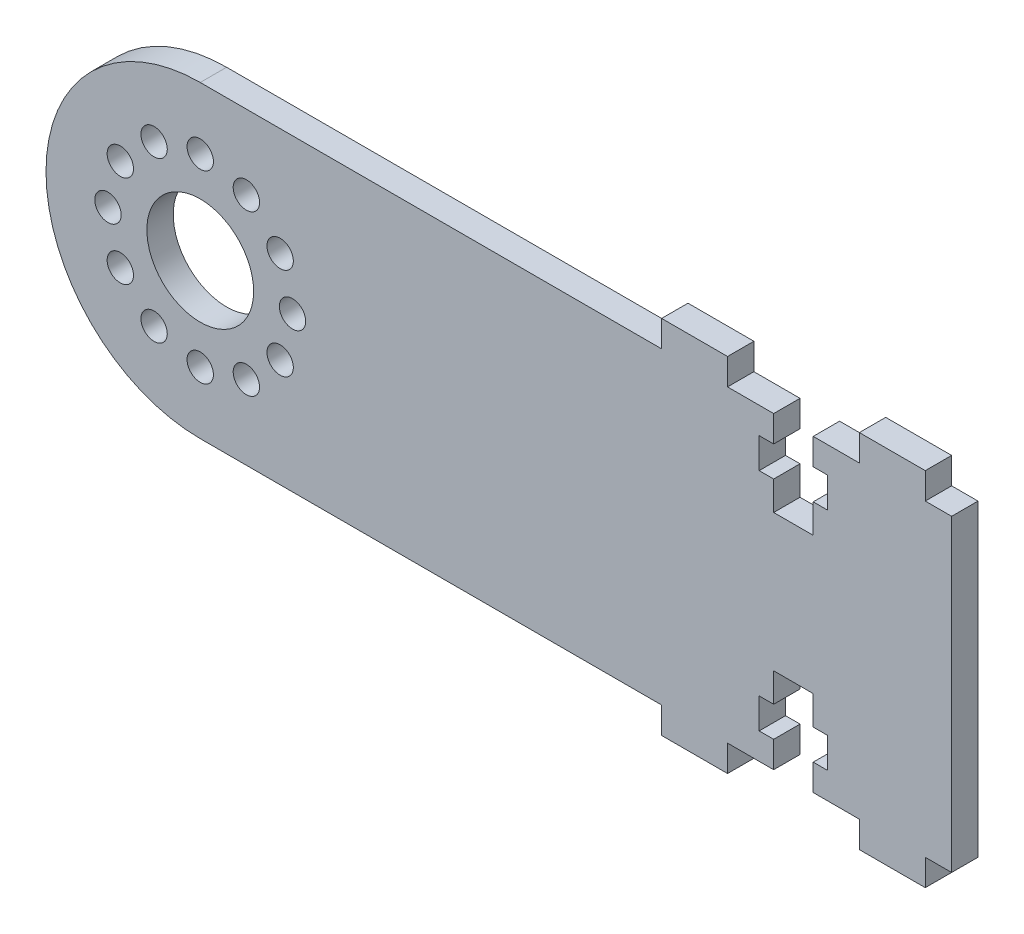
SolidWorks part; units mm, degrees
ref_plane "Front Plane" through (0, 0, 0) normal (0, 0, 1) x (1, 0, 0)
ref_plane "Top Plane" through (0, 0, 0) normal (0, 1, 0) x (1, 0, 0)
ref_plane "Right Plane" through (0, 0, 0) normal (1, 0, 0) x (0, 0, -1)
sketch "Sketch1" plane through (0, 0, 0) normal (0, 0, 1) x (1, 0, 0)
  line L0 (0, 11.7) -> (57, 11.7) construction
  line L1 (57, 11.7) -> (57, -11.7)
  line L2 (57, -11.7) -> (0, -11.7) construction
  line L3 (0, 0) -> (57, 0) construction
  line L4 (0, 11.7) -> (35, 11.7)
  line L5 (55, 11.7) -> (57, 11.7)
  line L6 (57, -11.7) -> (55, -11.7)
  line L7 (35, -11.7) -> (0, -11.7)
  arc A13 (0, 11.7) -> (0, -11.7) centre (0, 0) ccw
  point P2 (-45.8343, 7.2101)
  point P11 (-44.7074, 6.255)
  line B0 (0, 0) -> (7, 0) construction
  circle B1 centre (0, 0) radius 4.05
  circle B2 centre (7, 0) radius 1
  circle B3 centre (6.0622, -3.5) radius 1
  circle B4 centre (3.5, -6.0622) radius 1
  circle B5 centre (0, -7) radius 1
  circle B6 centre (-3.5, -6.0622) radius 1
  circle B7 centre (-6.0622, -3.5) radius 1
  circle B8 centre (-7, 0) radius 1
  circle B9 centre (-6.0622, 3.5) radius 1
  circle B10 centre (-3.5, 6.0622) radius 1
  circle B11 centre (0, 7) radius 1
  circle B12 centre (3.5, 6.0622) radius 1
  circle B13 centre (6.0622, 3.5) radius 1
  line B14 (45, -11.7) -> (45, -5.2) construction
  line B15 (43.5, -11.7) -> (40, -11.7)
  line B16 (40, -13.7) -> (35, -13.7)
  line B17 (35, -13.7) -> (35, -11.7)
  line B18 (40, -13.7) -> (40, -11.7)
  line B19 (46.5, -11.7) -> (50, -11.7)
  line B20 (50, -11.7) -> (50, -13.7)
  line B21 (50, -13.7) -> (55, -13.7)
  line B22 (55, -13.7) -> (55, -11.7)
  line B23 (43.5, -11.7) -> (46.5, -11.7) construction
  line B24 (46.5, -11.7) -> (46.5, -9.7)
  line B25 (46.5, -7.4) -> (47.6, -7.4)
  line B26 (42.4, -9.7) -> (42.4, -7.4)
  line B27 (47.6, -9.7) -> (46.5, -9.7)
  line B28 (46.5, -7.4) -> (46.5, -5.2)
  line B29 (46.5, -5.2) -> (43.5, -5.2)
  line B30 (43.5, -5.2) -> (43.5, -7.4)
  line B31 (43.5, -9.7) -> (42.4, -9.7)
  line B32 (47.6, -7.4) -> (47.6, -9.7)
  line B33 (42.4, -7.4) -> (43.5, -7.4)
  line B34 (43.5, -9.7) -> (43.5, -11.7)
  line B35 (45, -5.2) -> (45, -11.7) construction
  line B36 (45, 11.7) -> (45, 5.2) construction
  line B37 (43.5, 11.7) -> (40, 11.7)
  line B38 (40, 13.7) -> (35, 13.7)
  line B39 (35, 13.7) -> (35, 11.7)
  line B40 (40, 13.7) -> (40, 11.7)
  line B41 (46.5, 11.7) -> (50, 11.7)
  line B42 (50, 11.7) -> (50, 13.7)
  line B43 (50, 13.7) -> (55, 13.7)
  line B44 (55, 13.7) -> (55, 11.7)
  line B45 (43.5, 11.7) -> (46.5, 11.7) construction
  line B46 (46.5, 11.7) -> (46.5, 9.7)
  line B47 (46.5, 7.4) -> (47.6, 7.4)
  line B48 (42.4, 9.7) -> (42.4, 7.4)
  line B49 (47.6, 9.7) -> (46.5, 9.7)
  line B50 (46.5, 7.4) -> (46.5, 5.2)
  line B51 (46.5, 5.2) -> (43.5, 5.2)
  line B52 (43.5, 5.2) -> (43.5, 7.4)
  line B53 (43.5, 9.7) -> (42.4, 9.7)
  line B54 (47.6, 7.4) -> (47.6, 9.7)
  line B55 (42.4, 7.4) -> (43.5, 7.4)
  line B56 (43.5, 9.7) -> (43.5, 11.7)
  line B57 (45, 5.2) -> (45, 11.7) construction
  dimension "D1" = 23.4
  dimension "D2" = 45
  dimension "D3" = 12
sketch_block_instance "Block1-1"
sketch_block "Block1" parameters "D2"=2, "D3"=8.1, "D1"=7
sketch_block_instance "Block2-1"
sketch_block "Block2" parameters "D1"=10, "D2"=5, "D3"=2, "D4"=5.2, "D5"=3, "D6"=2.3, "D7"=2, "D8"=6.5
sketch_block_instance "Block2-2"
extrude "Boss-Extrude1" add sketch "Sketch1" along normal blind 2 contours B53 B56 B37 B40 B38 B39 L4 A13 L7 B17 B16 B18 B15 B34 B31 B26 B33 B30 B29 B28 B25 B32 B27 B24 B19 B20 B21 B22 L6 L1 L5 B44 B43 B42 B41 B46 B49 B54 B47 B50 B51 B52 B55 B48 B1 B2 B3
